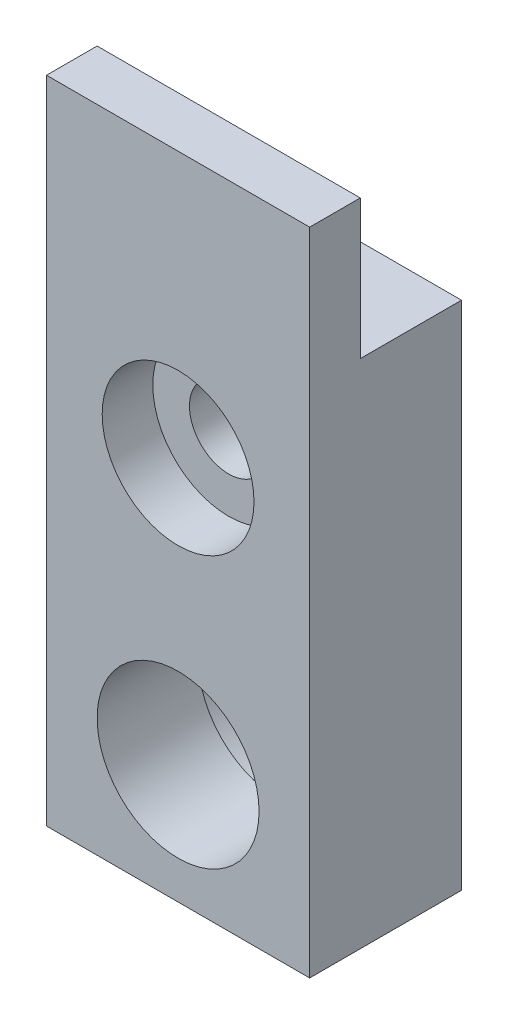
SolidWorks part; units mm, degrees
ref_plane "前视基准面" through (0, 0, 0) normal (0, 0, 1) x (1, 0, 0)
ref_plane "上视基准面" through (0, 0, 0) normal (0, 1, 0) x (1, 0, 0)
ref_plane "右视基准面" through (0, 0, 0) normal (1, 0, 0) x (0, 0, -1)
other "Configuration Table"
sketch "草图1" plane through (0, 0, 0) normal (0, 0, 1) x (1, 0, 0)
  line L1 (-15.3152, 4.7846) -> (-5.3152, 4.7846)
  line L2 (-15.3152, 4.7846) -> (-15.3152, -20.7154)
  line L3 (-15.3152, -20.7154) -> (-5.3152, -20.7154)
  line L4 (-5.3152, 4.7846) -> (-5.3152, -20.7154)
extrude "凸台-拉伸1" add sketch "草图1" along normal blind 15 contours L2 L1 L4 L3
sketch "草图2" plane through (0, 0, 15) normal (0, 0, 1) x (1, 0, 0)
  line L0 (-15.3152, 4.7846) -> (-5.3152, 4.7846)
  line L3 (-10.3152, 4.7846) -> (-10.3152, -5.7154)
  circle A0 centre (-10.3152, -5.7154) radius 1.55
extrude "切除-拉伸1" cut sketch "草图2" against normal blind 15
sketch "草图3" plane through (0, 0, 15) normal (0, 0, 1) x (1, 0, 0)
  circle A0 centre (-10.3152, -5.7154) radius 3
extrude "切除-拉伸2" cut sketch "草图3" against normal blind 3
sketch "草图4" plane through (0, 0, 15) normal (0, 0, 1) x (1, 0, 0)
  line L0 (-10.3152, -5.7154) -> (-10.3152, -16.2154)
  circle A0 centre (-10.3152, -16.2154) radius 3.5
extrude "切除-拉伸3" cut sketch "草图4" against normal blind 15 contours A0
sketch "草图5" plane through (-5.3152, 0, 0) normal (1, 0, 0) x (0, 0, -1)
  line L0 (-15, 4.7846) -> (0, 4.7846) construction
  line L1 (0, -20.7154) -> (-8, -20.7154)
  line L2 (0, -20.7154) -> (0, 4.7846)
  line L3 (0, 4.7846) -> (-8, 4.7846)
  line L4 (-8, -20.7154) -> (-8, 4.7846)
extrude "切除-拉伸4" cut sketch "草图5" against normal blind 15
sketch "草图6" plane through (0, 0, 8) normal (0, 0, -1) x (-1, 0, 0)
  circle A0 centre (10.3152, -16.2154) radius 4
extrude "切除-拉伸5" cut sketch "草图6" against normal blind 2
sketch "草图7" plane through (-5.3152, 0, 0) normal (1, 0, 0) x (0, 0, -1)
  line L0 (-8, -20.7154) -> (-8, -0.7154)
  line L1 (-8, 4.7846) -> (-8, -20.7154) construction
  line L2 (-15, 4.7846) -> (-8, 4.7846) construction
  line L3 (-8, -0.7154) -> (-12, -0.7154)
  line L4 (-8, -0.7154) -> (-8, 4.7846)
  line L5 (-8, 4.7846) -> (-12, 4.7846)
  line L6 (-12, -0.7154) -> (-12, 4.7846)
  line M6 (-8, -20.7154) -> (-8, 4.7846)
  line M7 (-8, 4.7846) -> (-15, 4.7846)
extrude "切除-拉伸6" cut sketch "草图7" against normal blind 15 contours L6 L3 M6 M7
sketch "草图8" plane through (0, 0, 15) normal (0, 0, 1) x (1, 0, 0)
  line L1 (-5.3152, 4.7846) -> (-5.1152, 4.7846)
  line L2 (-5.3152, 4.7846) -> (-5.3152, -20.7154)
  line L3 (-5.3152, -20.7154) -> (-5.1152, -20.7154)
  line L4 (-5.1152, 4.7846) -> (-5.1152, -20.7154)
  line L5 (-15.3152, 4.7846) -> (-15.5152, 4.7846)
  line L6 (-15.3152, 4.7846) -> (-15.3152, -20.7154)
  line L7 (-15.3152, -20.7154) -> (-15.5152, -20.7154)
  line L8 (-15.5152, 4.7846) -> (-15.5152, -20.7154)
  line L9 (-15.5152, -20.7154) -> (-5.1152, -20.7154)
  line L10 (-15.5152, -20.7154) -> (-15.5152, -20.9154)
  line L11 (-15.5152, -20.9154) -> (-5.1152, -20.9154)
  line L12 (-5.1152, -20.7154) -> (-5.1152, -20.9154)
  line M16 (-5.3152, -20.7154) -> (-5.3152, 4.7846)
  line M18 (-15.3152, 4.7846) -> (-15.3152, -20.7154)
extrude "凸台-拉伸2" add sketch "草图8" against normal blind 7 contours L5 L8 L7 M18 | L4 L1 L3 M16 | L10 L9 L12 L11
sketch "草图9" plane through (-15.5152, 0, 0) normal (-1, 0, 0) x (0, 0, 1)
  line L1 (8, 4.7846) -> (12, 4.7846)
  line L2 (8, 4.7846) -> (8, -0.7154)
  line L3 (8, -0.7154) -> (12, -0.7154)
  line L4 (12, 4.7846) -> (12, -0.7154)
extrude "切除-拉伸7" cut sketch "草图9" against normal blind 20 contours L2 L1 L4 L3
sketch "草图10" plane through (-15.5152, 0, 0) normal (-1, 0, 0) x (0, 0, 1)
  line L0 (8, -20.9154) -> (15, -20.9154) construction
  line L1 (15, 4.7846) -> (14, 4.7846)
  line L2 (15, 4.7846) -> (15, -20.9154)
  line L3 (15, -20.9154) -> (14, -20.9154)
  line L4 (14, 4.7846) -> (14, -20.9154)
extrude "切除-拉伸9" cut sketch "草图10" against normal blind 15
sketch "草图12" plane through (0, 0, 14) normal (0, 0, 1) x (1, 0, 0)
  circle A0 centre (-10.3152, -16.2154) radius 3.5
  circle A1 centre (-10.3152, -16.2154) radius 3.2
extrude "凸台-拉伸4" add sketch "草图12" against normal blind 4 contours A1 | A0
